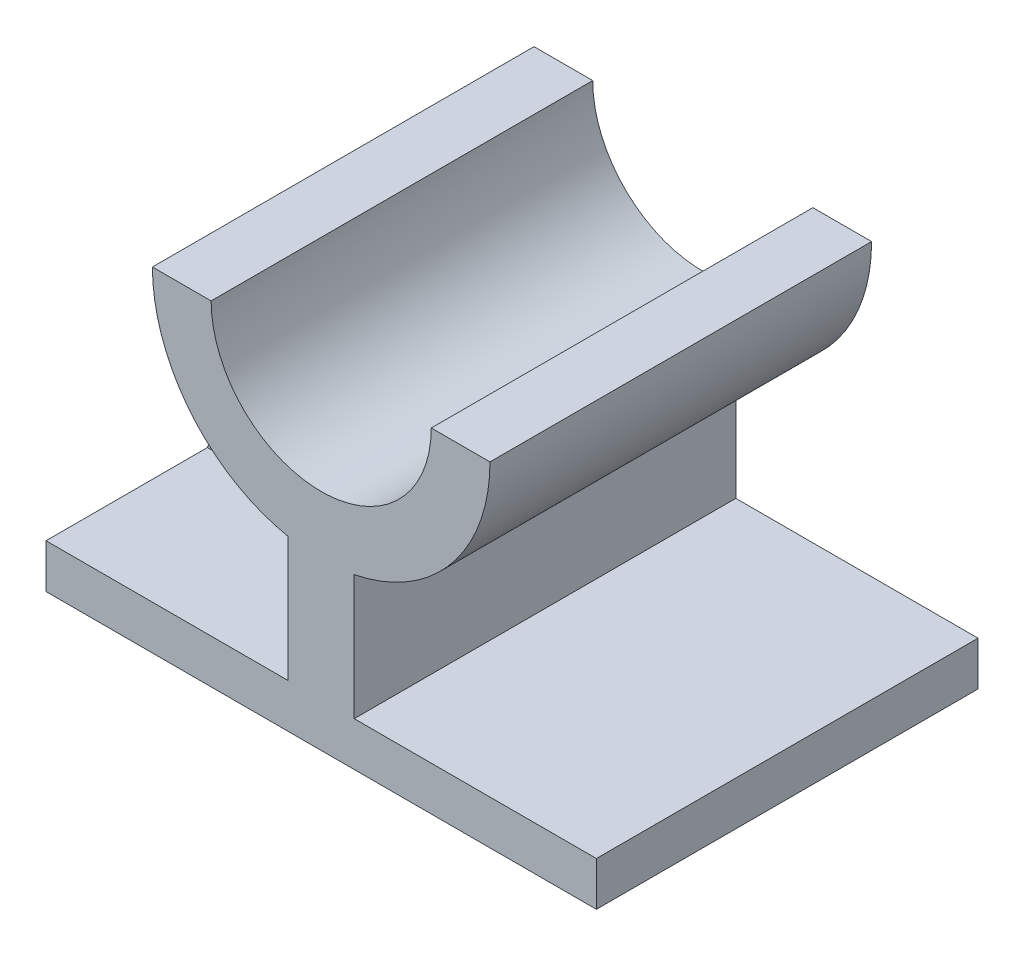
SolidWorks part; units mm, degrees
ref_plane "Front Plane" through (0, 0, 0) normal (0, 0, 1) x (1, 0, 0)
ref_plane "Top Plane" through (0, 0, 0) normal (0, 1, 0) x (1, 0, 0)
ref_plane "Right Plane" through (0, 0, 0) normal (1, 0, 0) x (0, 0, -1)
sketch "Sketch1" plane through (0, 0, 0) normal (0, 0, 1) x (1, 0, 0)
  line L0 (-63.135, 0) -> (686.865, 0)
  line L1 (686.865, 0) -> (686.865, 60)
  line L2 (686.865, 60) -> (356.865, 60)
  line L3 (-63.135, 0) -> (-63.135, 60)
  line L4 (-63.135, 60) -> (266.865, 60)
  line L5 (311.865, -184.6805) -> (311.865, 589.8357) construction
  line L6 (356.865, 60) -> (356.865, 230)
  line L7 (266.865, 60) -> (266.865, 230)
  line L8 (709.0991, 455.5549) -> (-84.239, 455.5549) construction
  line L9 (81.865, 455.5549) -> (161.865, 455.5549)
  line L10 (461.865, 455.5549) -> (541.865, 455.5549)
  arc A0 (81.865, 455.5549) -> (266.865, 230) centre (311.865, 455.5549) ccw
  arc A1 (161.865, 455.5549) -> (461.865, 455.5549) centre (311.865, 455.5549) ccw
  arc A2 (356.865, 230) -> (541.865, 455.5549) centre (311.865, 455.5549) ccw
  dimension "D1" = 170
  dimension "D2" = 60
extrude "Boss-Extrude1" add sketch "Sketch1" against normal blind 520
ref_plane "Plane3" through (0, 0, -260) normal (0, 0, -1) x (-1, 0, 0)
sketch "Sketch14" plane through (0, 0, -260) normal (0, 0, -1) x (-1, 0, 0)
  line L0 (-81.865, 455.5549) -> (63.135, 60)
rib "Rib15" sketch "Sketch14" sketch "Sketch14" thickness 80 extrusion direction parallel to sketch draft on no parameters "D1"=80
